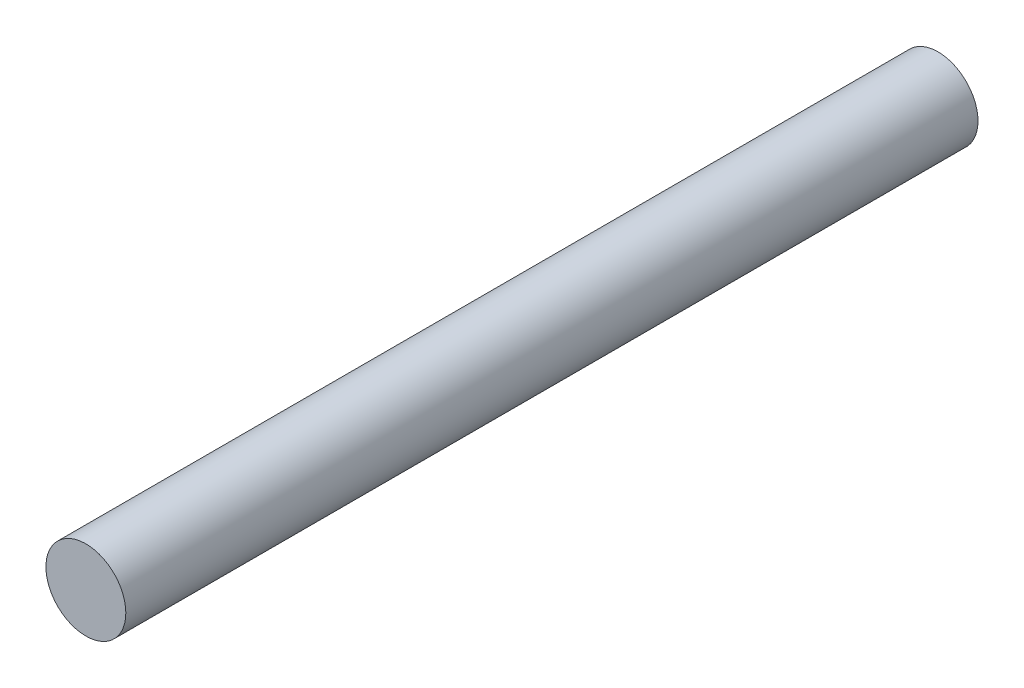
SolidWorks part; units mm, degrees
material "LW-PLA"
ref_plane "Front Plane" through (0, 0, 0) normal (0, 0, 1) x (1, 0, 0)
ref_plane "Top Plane" through (0, 0, 0) normal (0, 1, 0) x (1, 0, 0)
ref_plane "Right Plane" through (0, 0, 0) normal (1, 0, 0) x (0, 0, -1)
sketch "Sketch1" plane through (0, 0, 0) normal (0, 0, 1) x (1, 0, 0)
  circle A0 centre (0, 0) radius 0.75
  dimension "D1" = 1.5
extrude "Boss-Extrude1" add sketch "Sketch1" along normal blind 16
